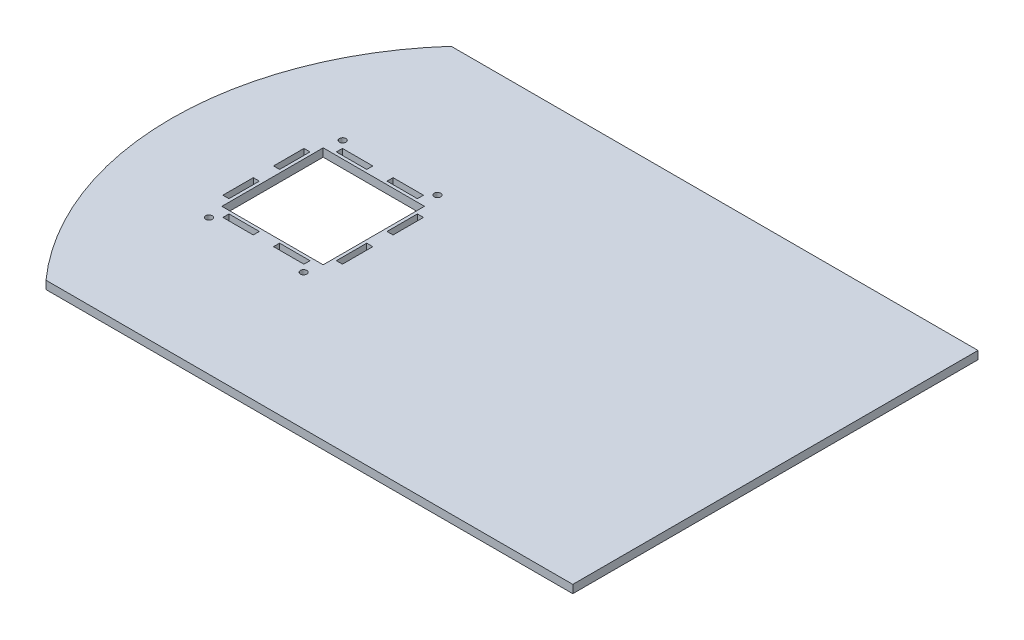
SolidWorks part; units mm, degrees
ref_plane "Front Plane" through (0, 0, 0) normal (0, 0, 1) x (1, 0, 0)
ref_plane "Top Plane" through (0, 0, 0) normal (0, 1, 0) x (1, 0, 0)
ref_plane "Right Plane" through (0, 0, 0) normal (1, 0, 0) x (0, 0, -1)
sketch "Sketch1" plane through (37.5591, 0, 0) normal (0, 1, 0) x (1, 0, 0)
  line L0 (-199.9795, 77.6539) -> (-199.9795, 27.6539)
  line L4 (48.2171, 152.6539) -> (48.2171, -47.3461)
  line L5 (-199.9795, 27.6539) -> (-149.9795, 27.6539)
  line L6 (-149.9795, 27.6539) -> (-149.9795, 77.6539)
  line L7 (-149.9795, 77.6539) -> (-199.9795, 77.6539)
  line L8 (-179.9795, 82.1539) -> (-179.9795, 79.1539)
  line L9 (-211.7829, 152.6539) -> (48.2171, 152.6539)
  line L10 (-211.7829, -47.3461) -> (48.2171, -47.3461)
  line L11 (-194.9795, 26.1539) -> (-194.9795, 23.1539)
  line L12 (-194.9795, 23.1539) -> (-179.9795, 23.1539)
  line L13 (-179.9795, 23.1539) -> (-179.9795, 26.1539)
  line L14 (-179.9795, 26.1539) -> (-194.9795, 26.1539)
  line L15 (-169.9795, 23.1539) -> (-169.9795, 26.1539)
  line L16 (-154.9795, 23.1539) -> (-169.9795, 23.1539)
  line L17 (-154.9795, 26.1539) -> (-154.9795, 23.1539)
  line L18 (-169.9795, 26.1539) -> (-154.9795, 26.1539)
  line L19 (-194.9795, 82.1539) -> (-179.9795, 82.1539)
  line L20 (-194.9795, 79.1539) -> (-194.9795, 82.1539)
  line L21 (-179.9795, 79.1539) -> (-194.9795, 79.1539)
  line L22 (-154.9795, 79.1539) -> (-154.9795, 82.1539)
  line L23 (-154.9795, 82.1539) -> (-169.9795, 82.1539)
  line L24 (-169.9795, 79.1539) -> (-154.9795, 79.1539)
  line L25 (-169.9795, 82.1539) -> (-169.9795, 79.1539)
  line L30 (-148.4795, 47.6539) -> (-145.4795, 47.6539)
  line L31 (-145.4795, 47.6539) -> (-145.4795, 32.6539)
  line L32 (-145.4795, 32.6539) -> (-148.4795, 32.6539)
  line L33 (-148.4795, 32.6539) -> (-148.4795, 47.6539)
  line L34 (-145.4795, 72.6539) -> (-148.4795, 72.6539)
  line L35 (-145.4795, 57.6539) -> (-145.4795, 72.6539)
  line L36 (-148.4795, 72.6539) -> (-148.4795, 57.6539)
  line L37 (-148.4795, 57.6539) -> (-145.4795, 57.6539)
  line L40 (-204.4795, 32.6539) -> (-201.4795, 32.6539)
  line L41 (-201.4795, 47.6539) -> (-204.4795, 47.6539)
  line L42 (-204.4795, 47.6539) -> (-204.4795, 32.6539)
  line L43 (-201.4795, 32.6539) -> (-201.4795, 47.6539)
  line L44 (-201.4795, 57.6539) -> (-204.4795, 57.6539)
  line L45 (-204.4795, 72.6539) -> (-201.4795, 72.6539)
  line L46 (-204.4795, 57.6539) -> (-204.4795, 72.6539)
  line L47 (-201.4795, 72.6539) -> (-201.4795, 57.6539)
  circle A0 centre (-198.3531, 19.6539) radius 1.6
  circle A5 centre (-151.6058, 19.6539) radius 1.6
  circle A6 centre (-198.3531, 85.6539) radius 1.6
  circle A7 centre (-151.6058, 85.6539) radius 1.6
  arc A8 (-249.9795, 52.6539) -> (-211.7829, 152.6539) centre (-99.9795, 52.6539) cw
  arc A9 (-249.9795, 52.6539) -> (-211.7829, -47.3461) centre (-99.9795, 52.6539) ccw
  point P7 (-199.9795, 52.6539)
  point P27 (-194.9795, 24.6539)
  point P43 (-146.9795, 47.6539)
  dimension "D7" = 3.2
  dimension "D3" = 260
  dimension "D4" = 260
  dimension "D5" = 50
  dimension "D6" = 50
  dimension "D8" = 3
  dimension "D9" = 3
  dimension "D10" = 15
  dimension "D11" = 1.5
  dimension "D12" = 1.5
  dimension "D13" = 1.5
  dimension "D14" = 8
  dimension "D15" = 8
  dimension "D16" = 8
  dimension "D17" = 1.5
  dimension "D18" = 15
  dimension "D19" = 200
  dimension "D20" = 3
extrude "Boss-Extrude1" add sketch "Sketch1" along normal blind 4
